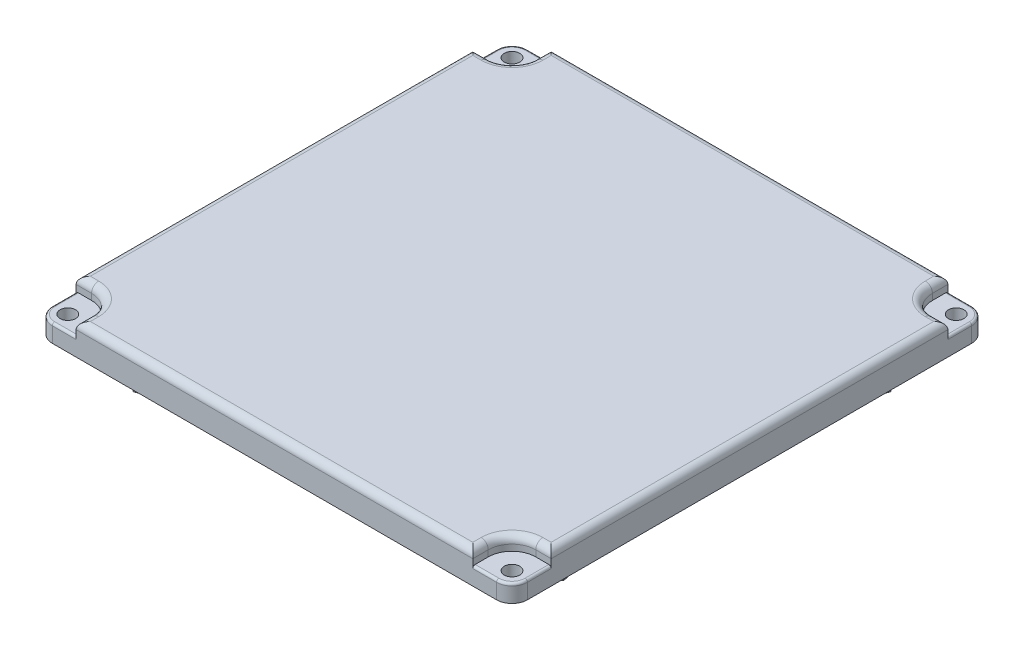
SolidWorks part; units mm, degrees
ref_plane "Front Plane" through (0, 0, 0) normal (0, 0, 1) x (1, 0, 0)
ref_plane "Top Plane" through (0, 0, 0) normal (0, 1, 0) x (1, 0, 0)
ref_plane "Right Plane" through (0, 0, 0) normal (1, 0, 0) x (0, 0, -1)
sketch "Sketch1" plane through (0, 0, 0) normal (0, 1, 0) x (1, 0, 0)
  line L1 (-50, -50) -> (50, -50)
  line L2 (-50, -50) -> (-50, 50)
  line L3 (-50, 50) -> (50, 50)
  line L4 (50, -50) -> (50, 50)
  line L5 (-50, -50) -> (50, 50) construction
  line L6 (-50, 50) -> (50, -50) construction
  point P0 (0, 0)
  dimension "D1" = 100
  dimension "D2" = 100
extrude "Boss-Extrude1" add sketch "Sketch1" along normal blind 53.5
sketch "Sketch2" plane through (0, 0, 0) normal (0, -1, 0) x (1, 0, 0)
  line L0 (0, 0) -> (0, -50)
  line L1 (50, -50) -> (-50, -50) construction
  line L2 (-20.55, -50) -> (20.55, -50)
  line L3 (-20.55, -50) -> (-20.55, -56.9738)
  line L4 (-33.15, -50) -> (-33.15, -56.9738)
  line L6 (-33.15, -50) -> (-33.15, -46.9276)
  line L7 (-33.15, -46.9276) -> (-20.55, -46.9276)
  line L8 (-20.55, -46.9276) -> (-20.55, -50)
  line L9 (20.55, -50) -> (20.55, -56.9738)
  line L10 (33.15, -50) -> (33.15, -56.9738)
  line L11 (33.15, -50) -> (33.15, -46.9276)
  line L12 (33.15, -46.9276) -> (20.55, -46.9276)
  line L13 (20.55, -46.9276) -> (20.55, -50)
  line L14 (-18.3596, 0) -> (18.3596, 0)
  line L15 (20.55, 46.9276) -> (20.55, 50)
  line L16 (33.15, 46.9276) -> (20.55, 46.9276)
  line L17 (33.15, 50) -> (33.15, 46.9276)
  line L18 (33.15, 50) -> (33.15, 56.9738)
  line L19 (20.55, 50) -> (20.55, 56.9738)
  line L20 (-20.55, 50) -> (-20.55, 56.9738)
  line L21 (-33.15, 50) -> (-33.15, 56.9738)
  line L22 (-33.15, 50) -> (-33.15, 46.9276)
  line L23 (-33.15, 46.9276) -> (-20.55, 46.9276)
  line L24 (-20.55, 46.9276) -> (-20.55, 50)
  arc A0 (-33.15, -56.9738) -> (-20.55, -56.9738) centre (-26.85, -56.9738) ccw
  circle A1 centre (-26.85, -56.9738) radius 2.5
  circle A2 centre (26.85, -56.9738) radius 2.5
  arc A3 (33.15, -56.9738) -> (20.55, -56.9738) centre (26.85, -56.9738) cw
  circle A4 centre (26.85, 56.9738) radius 2.5
  arc A5 (33.15, 56.9738) -> (20.55, 56.9738) centre (26.85, 56.9738) ccw
  circle A6 centre (-26.85, 56.9738) radius 2.5
  arc A7 (-33.15, 56.9738) -> (-20.55, 56.9738) centre (-26.85, 56.9738) cw
  point P24 (0, 0)
  line M18 (50, 50) -> (-50, 50)
  line M20 (-50, -50) -> (50, -50)
  dimension "D3" = 12.6
  dimension "D2" = 20.55
extrude "Boss-Extrude2" add sketch "Sketch2" against normal blind 4 contours A3 L10 L9 A2 M20 | L4 A0 L3 A1 M20 | L23 L24 L22 M18 | A7 L21 L20 A6 M18 | L18 A5 L19 A4 M18 | L17 L15 L16 M18 | L12 L13 L11 M20 | L8 L7 L6 M20
sketch "Sketch3" plane through (0, 53.5, 0) normal (0, 1, 0) x (1, 0, 0)
  line L0 (-35.565, 48) -> (35.565, 48)
  line L1 (-48, -48) -> (48, -48)
  line L2 (-48, -48) -> (-48, 48)
  line L3 (-48, 48) -> (48, 48)
  line L4 (48, -48) -> (48, 48)
  line L5 (-48, -48) -> (48, 48) construction
  line L6 (-48, 48) -> (48, -48) construction
  line L7 (-48, -35.565) -> (-48, 35.565)
  line L8 (-48, 35.565) -> (-35.565, 48)
  line L9 (0, 0) -> (0, -12.9219)
  line L10 (0, -29.425) -> (0, 29.425) construction
  line L11 (0, 0) -> (14.2301, 0)
  line L12 (-29.425, 0) -> (29.425, 0) construction
  line L13 (-48, -35.565) -> (-35.565, -48)
  line L14 (48, -35.565) -> (35.565, -48)
  line L15 (48, 35.565) -> (35.565, 48)
  point P0 (0, 0)
  point P9 (0, 48)
  point P12 (-48, 0)
  point P17 (0, 0)
  dimension "D1" = 11.6213
  dimension "D2" = 96
  dimension "D3" = 71.13
extrude "Cut-Extrude1" cut sketch "Sketch3" against normal blind 47.5
fillet "Fillet1" radius 3.25 4 edges at (50, 26.75, 50) (-50, 26.75, 50) (-50, 26.75, -50) (50, 26.75, -50)
fillet "Fillet2" radius 3 4 edges at (26.85, 4, -50) (-26.85, 4, -50) (-26.85, 4, 50) (26.85, 4, 50)
sketch "Sketch4" plane through (0, 53.5, 0) normal (0, 1, 0) x (1, 0, 0)
  line L0 (-49.0481, 49.0481) -> (-46.75, 46.75)
  line L1 (0, 0) -> (0, 11.199)
  line L2 (0, -29.425) -> (0, 29.425) construction
  line L3 (0, 0) -> (-16.0806, 0)
  line L4 (-29.425, 0) -> (29.425, 0) construction
  arc A0 (-46.75, 50) -> (-50, 46.75) centre (-46.75, 46.75) ccw construction
  circle A1 centre (-46.75, 46.75) radius 1.625
  circle A2 centre (46.75, 46.75) radius 1.625
  circle A3 centre (46.75, -46.75) radius 1.625
  circle A4 centre (-46.75, -46.75) radius 1.625
extrude "Cut-Extrude2" cut sketch "Sketch4" against normal blind 14
fillet "Fillet3" radius 3 12 edges at (39.95, 0, -50) (49.0481, 0, -49.0481) (50, 0, 0) (49.0481, 0, 49.0481) (-39.95, 0, -50) (-49.0481, 0, -49.0481) (-50, 0, 0) (-49.0481, 0, 49.0481) (0, 0, -50) (39.95, 0, 50) (-39.95, 0, 50) (0, 0, 50)
sketch "Sketch8" plane through (0, 53.5, 0) normal (0, 1, 0) x (1, 0, 0)
  line L8 (-46.75, -50) -> (46.75, -50)
  line L9 (50, -46.75) -> (50, 46.75)
  line L10 (46.75, 50) -> (-46.75, 50)
  line L11 (-50, 46.75) -> (-50, -46.75)
  line L12 (-46.75, -50) -> (46.75, -50)
  line L13 (50, -46.75) -> (50, 46.75)
  line L14 (46.75, 50) -> (-46.75, 50)
  line L15 (-50, 46.75) -> (-50, -46.75)
  line L20 (-46.75, -50) -> (46.75, -50)
  line L21 (50, -46.75) -> (50, 46.75)
  line L22 (46.75, 50) -> (-46.75, 50)
  line L23 (-50, 46.75) -> (-50, -46.75)
  arc A6 (46.75, -50) -> (50, -46.75) centre (46.75, -46.75) ccw
  arc A7 (50, 46.75) -> (46.75, 50) centre (46.75, 46.75) ccw
  arc A8 (46.75, -50) -> (50, -46.75) centre (46.75, -46.75) ccw
  arc A9 (50, 46.75) -> (46.75, 50) centre (46.75, 46.75) ccw
  arc A10 (-46.75, 50) -> (-50, 46.75) centre (-46.75, 46.75) ccw
  arc A11 (-50, -46.75) -> (-46.75, -50) centre (-46.75, -46.75) ccw
  arc A12 (46.75, -50) -> (50, -46.75) centre (46.75, -46.75) ccw
  arc A13 (50, 46.75) -> (46.75, 50) centre (46.75, 46.75) ccw
  arc A14 (-46.75, 50) -> (-50, 46.75) centre (-46.75, 46.75) ccw
  arc A15 (-50, -46.75) -> (-46.75, -50) centre (-46.75, -46.75) ccw
  arc A16 (-46.75, 50) -> (-50, 46.75) centre (-46.75, 46.75) ccw
  arc A17 (-50, -46.75) -> (-46.75, -50) centre (-46.75, -46.75) ccw
  circle M9 centre (46.75, -46.75) radius 1.625
  circle M10 centre (-46.75, 46.75) radius 1.625
  line M11 (35.565, 48) -> (48, 35.565)
  line M12 (48, 35.565) -> (48, -35.565)
  line M13 (48, -35.565) -> (35.565, -48)
  line M14 (35.565, -48) -> (-35.565, -48)
  line M15 (-35.565, -48) -> (-48, -35.565)
  line M16 (-48, -35.565) -> (-48, 35.565)
  line M17 (-48, 35.565) -> (-35.565, 48)
  line M18 (-35.565, 48) -> (35.565, 48)
  line M19 (-46.75, -50) -> (46.75, -50)
  arc M20 (46.75, -50) -> (50, -46.75) centre (46.75, -46.75) ccw
  line M21 (50, -46.75) -> (50, 46.75)
  arc M22 (50, 46.75) -> (46.75, 50) centre (46.75, 46.75) ccw
  line M23 (46.75, 50) -> (-46.75, 50)
  arc M24 (-46.75, 50) -> (-50, 46.75) centre (-46.75, 46.75) ccw
  line M25 (-50, 46.75) -> (-50, -46.75)
  arc M26 (-50, -46.75) -> (-46.75, -50) centre (-46.75, -46.75) ccw
  circle M27 centre (46.75, 46.75) radius 1.625
  circle M28 centre (-46.75, -46.75) radius 1.625
  dimension "D1" = 0
  dimension "D2" = 0
extrude "Boss-Extrude3" add sketch "Sketch8" along normal blind 6.5 contours M11 M18 M17 M16 M15 M14 M13 M12 | M26 M19 M20 M21 M22 M23 M24 M25 M10 M27 M28 M18 M11 M12 M13 M14 M15 M16 M17 M9
sketch "Sketch10" plane through (0, 53.5, 0) normal (0, -1, 0) x (1, 0, 0)
  line L1 (-79.706, -65.9825) -> (79.706, -65.9825)
  line L2 (-79.706, -65.9825) -> (-79.706, 65.9825)
  line L3 (-79.706, 65.9825) -> (79.706, 65.9825)
  line L4 (79.706, -65.9825) -> (79.706, 65.9825)
  line L5 (-79.706, -65.9825) -> (79.706, 65.9825) construction
  line L6 (-79.706, 65.9825) -> (79.706, -65.9825) construction
  point P0 (0, 0)
extrude "Cut-Extrude3" cut sketch "Sketch10" along normal blind 205.5
sketch "Sketch11" plane through (0, 60, 0) normal (0, 1, 0) x (1, 0, 0)
  line L0 (-46.75, 41.75) -> (-50, 41.75)
  line L1 (0, 0) -> (-14.5888, 0)
  line L2 (-14.5888, 0) -> (0, 0)
  line L3 (-41.75, 50) -> (-41.75, 46.75)
  line L4 (-41.75, 46.75) -> (-41.75, 50)
  line L5 (46.75, 50) -> (-46.75, 50) construction
  line L6 (-41.75, 50) -> (-50.5497, 50)
  line L7 (-50, -41.75) -> (-50, -46.75)
  line L8 (-50, -46.75) -> (-50, -50)
  line L9 (-41.75, -50) -> (-50.5497, -50)
  line L10 (-50, 46.75) -> (-50, -46.75) construction
  line L11 (-50, 41.75) -> (-50, 46.75)
  line L12 (-50, 46.75) -> (-50, 50)
  line L13 (-41.75, -50) -> (-41.75, -46.75)
  line L14 (-46.75, -41.75) -> (-50, -41.75)
  line L15 (0, 0) -> (0, -19.6564)
  line L16 (41.75, 50) -> (50.5497, 50)
  line L17 (50, 46.75) -> (50, 50)
  line L18 (50, 41.75) -> (50, 46.75)
  line L19 (46.75, 41.75) -> (50, 41.75)
  line L20 (41.75, 50) -> (41.75, 46.75)
  line L21 (41.75, -50) -> (41.75, -46.75)
  line L22 (50, -46.75) -> (50, -50)
  line L23 (50, -41.75) -> (50, -46.75)
  line L24 (46.75, -41.75) -> (50, -41.75)
  line L25 (41.75, -50) -> (50.5497, -50)
  arc A0 (-46.75, 41.75) -> (-41.75, 46.75) centre (-46.75, 46.75) ccw
  arc A1 (-46.75, -41.75) -> (-41.75, -46.75) centre (-46.75, -46.75) cw
  arc A2 (46.75, 41.75) -> (41.75, 46.75) centre (46.75, 46.75) cw
  arc A3 (46.75, -41.75) -> (41.75, -46.75) centre (46.75, -46.75) ccw
  circle M13 centre (-46.75, 46.75) radius 1.625
  circle M14 centre (46.75, 46.75) radius 1.625
  circle M15 centre (-46.75, -46.75) radius 1.625
  arc M16 (-50, -46.75) -> (-46.75, -50) centre (-46.75, -46.75) ccw
  line M17 (-46.75, -50) -> (46.75, -50)
  arc M18 (46.75, -50) -> (50, -46.75) centre (46.75, -46.75) ccw
  line M19 (50, -46.75) -> (50, 46.75)
  arc M20 (50, 46.75) -> (46.75, 50) centre (46.75, 46.75) ccw
  line M21 (46.75, 50) -> (-46.75, 50)
  arc M22 (-46.75, 50) -> (-50, 46.75) centre (-46.75, 46.75) ccw
  line M23 (-50, 46.75) -> (-50, -46.75)
  circle M24 centre (46.75, -46.75) radius 1.625
extrude "Cut-Extrude4" cut sketch "Sketch11" against normal blind 2.8 contours A1 L14 L13 M23 M16 M17 M15 | L0 A0 L3 M21 M22 M23 M13 | A2 L19 L20 M19 M20 M21 M14 | L24 A3 L21 M17 M18 M19 M24
fillet "Fillet4" radius 1.5 16 edges at (41.75, 60, 48.375) (0, 60, 50) (-41.75, 60, 48.375) (-43.2145, 60, 43.2145) (-48.375, 60, 41.75) (-50, 60, 0) (-48.375, 60, -41.75) (-43.2145, 60, -43.2145) (-41.75, 60, -48.375) (0, 60, -50) (41.75, 60, -48.375) (43.2145, 60, -43.2145) (48.375, 60, -41.75) (50, 60, 0) (48.375, 60, 41.75) (43.2145, 60, 43.2145)
fillet "Fillet5" radius 0.5 12 edges at (-44.25, 57.2, 50) (-49.0481, 57.2, 49.0481) (-50, 57.2, -44.25) (-49.0481, 57.2, -49.0481) (44.25, 57.2, 50) (49.0481, 57.2, 49.0481) (-50, 57.2, 44.25) (-44.25, 57.2, -50) (50, 57.2, 44.25) (50, 57.2, -44.25) (49.0481, 57.2, -49.0481) (44.25, 57.2, -50)
sketch "Sketch12" plane through (0, 53.5, 0) normal (0, -1, 0) x (1, 0, 0)
  line L16 (34.4466, -45.3) -> (45.3, -34.4466)
  line L17 (45.3, -34.4466) -> (45.3, 34.4466)
  line L18 (45.3, 34.4466) -> (34.4466, 45.3)
  line L19 (34.4466, 45.3) -> (-34.4466, 45.3)
  line L20 (-34.4466, 45.3) -> (-45.3, 34.4466)
  line L21 (-45.3, 34.4466) -> (-45.3, -34.4466)
  line L22 (-45.3, -34.4466) -> (-34.4466, -45.3)
  line L23 (-34.4466, -45.3) -> (34.4466, -45.3)
  line L24 (-49.8, 46.75) -> (-49.8, -46.75)
  line L28 (-49.8, 46.75) -> (-49.8, -46.75)
  line L40 (33.4111, -42.8) -> (42.8, -33.4111)
  line L41 (42.8, -33.4111) -> (42.8, 33.4111)
  line L42 (42.8, 33.4111) -> (33.4111, 42.8)
  line L43 (33.4111, 42.8) -> (-33.4111, 42.8)
  line L44 (-46.75, -49.8) -> (46.75, -49.8)
  line L45 (-46.75, -49.8) -> (46.75, -49.8)
  line L46 (49.8, -46.75) -> (49.8, 46.75)
  line L47 (49.8, -46.75) -> (49.8, 46.75)
  line L48 (46.75, 49.8) -> (-46.75, 49.8)
  line L50 (46.75, 49.8) -> (-46.75, 49.8)
  line L52 (-33.4111, 42.8) -> (-42.8, 33.4111)
  line L54 (-42.8, 33.4111) -> (-42.8, -33.4111)
  line L56 (-42.8, -33.4111) -> (-33.4111, -42.8)
  line L58 (-33.4111, -42.8) -> (33.4111, -42.8)
  arc A4 (-46.75, 49.8) -> (-49.8, 46.75) centre (-46.75, 46.75) ccw
  arc A8 (-49.8, -46.75) -> (-46.75, -49.8) centre (-46.75, -46.75) ccw
  arc A10 (-49.8, -46.75) -> (-46.75, -49.8) centre (-46.75, -46.75) ccw
  arc A12 (46.75, -49.8) -> (49.8, -46.75) centre (46.75, -46.75) ccw
  arc A13 (46.75, -49.8) -> (49.8, -46.75) centre (46.75, -46.75) ccw
  arc A14 (49.8, 46.75) -> (46.75, 49.8) centre (46.75, 46.75) ccw
  dimension "D1" = 0.2
  dimension "D2" = 2.5
extrude "Boss-Extrude4" add sketch "Sketch12" along normal blind 5 contours L22 L23 L16 L17 L18 L19 L20 L21 L58 L56 L54 L52 L43 L42 L41 L40
fillet "Fillet6" radius 0.5 8 edges at (-42.8, 53.5, 0) (-38.1055, 53.5, 38.1055) (0, 53.5, 42.8) (38.1055, 53.5, 38.1055) (42.8, 53.5, 0) (38.1055, 53.5, -38.1055) (0, 53.5, -42.8) (-38.1055, 53.5, -38.1055)
sketch "Sketch13" plane through (-45.3, 0, 0) normal (-1, 0, 0) x (0, 0, 1)
  line L0 (-34.4466, 48.5) -> (-26.4466, 50.5)
  line L1 (-26.4466, 50.5) -> (26.4466, 50.5)
  line L2 (26.4466, 50.5) -> (34.4466, 48.5)
  line L3 (45.3, 48.5) -> (34.4466, 48.5) construction
  line L4 (34.4466, 48.5) -> (34.4466, 53.5) construction
  line L5 (34.4466, 53.5) -> (-34.4466, 53.5) construction
  line L6 (-34.4466, 48.5) -> (-34.4466, 53.5) construction
  line L7 (-34.4466, 48.5) -> (34.4466, 48.5)
  dimension "D1" = 3
  dimension "D2" = 8
  dimension "D3" = 8
extrude "Cut-Extrude5" cut sketch "Sketch13" against normal blind 130
sketch "Sketch14" plane through (0, 0, 45.3) normal (0, 0, 1) x (1, 0, 0)
  line L0 (-34.4466, 48.5) -> (-26.7007, 50.5)
  line L1 (-26.7007, 50.5) -> (28.5224, 50.5)
  line L2 (28.5224, 50.5) -> (36.2683, 48.5)
  line L3 (34.4466, 48.5) -> (-34.4466, 48.5) construction
  line L5 (34.4466, 53.5) -> (-34.4466, 53.5) construction
  line L6 (-34.4466, 48.5) -> (36.2683, 48.5)
  dimension "D1" = 3
  dimension "D2" = 8
  dimension "D3" = 8
extrude "Cut-Extrude6" cut sketch "Sketch14" against normal blind 130 contours L6 L2 L1 L0
